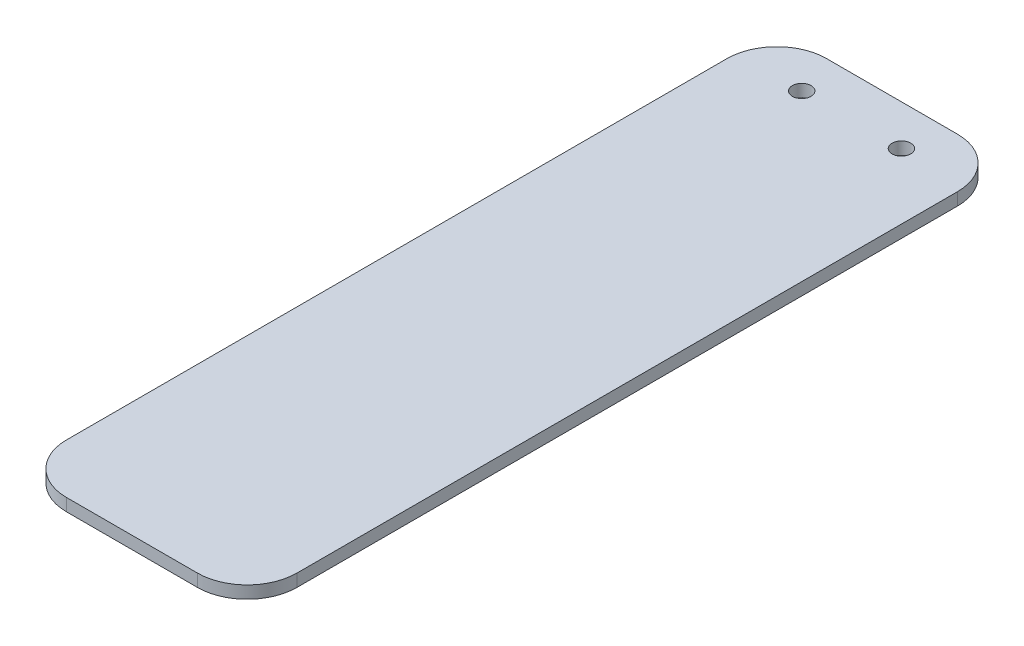
SolidWorks part; units mm, degrees
ref_plane "Front Plane" through (0, 0, 0) normal (0, 0, 1) x (1, 0, 0)
ref_plane "Top Plane" through (0, 0, 0) normal (0, 1, 0) x (1, 0, 0)
ref_plane "Right Plane" through (0, 0, 0) normal (1, 0, 0) x (0, 0, -1)
sketch "Sketch1" plane through (0, 0, 0) normal (0, 1, 0) x (1, 0, 0)
  line L0 (0, 61) -> (37, 61) construction
  line L1 (8, 0) -> (29, 0)
  line L2 (0, 8) -> (0, 114)
  line L3 (8, 122) -> (29, 122)
  line L4 (37, 8) -> (37, 114)
  line L5 (18.5, 122) -> (18.5, 0) construction
  circle A2 centre (26.5, 115.5) radius 1.5
  circle A3 centre (10.5, 115.5) radius 1.5
  arc A4 (8, 0) -> (0, 8) centre (8, 8) cw
  arc A5 (29, 0) -> (37, 8) centre (29, 8) ccw
  arc A6 (29, 122) -> (37, 114) centre (29, 114) cw
  arc A7 (0, 114) -> (8, 122) centre (8, 114) cw
  point P15 (0, 0)
  point P18 (37, 0)
  point P23 (0, 122)
  dimension "D3" = 3
  dimension "D6" = 8
  dimension "D1" = 37
  dimension "D2" = 122
  dimension "D4" = 6.5
  dimension "D5" = 8
extrude "Boss-Extrude1" add sketch "Sketch1" along normal blind 2
